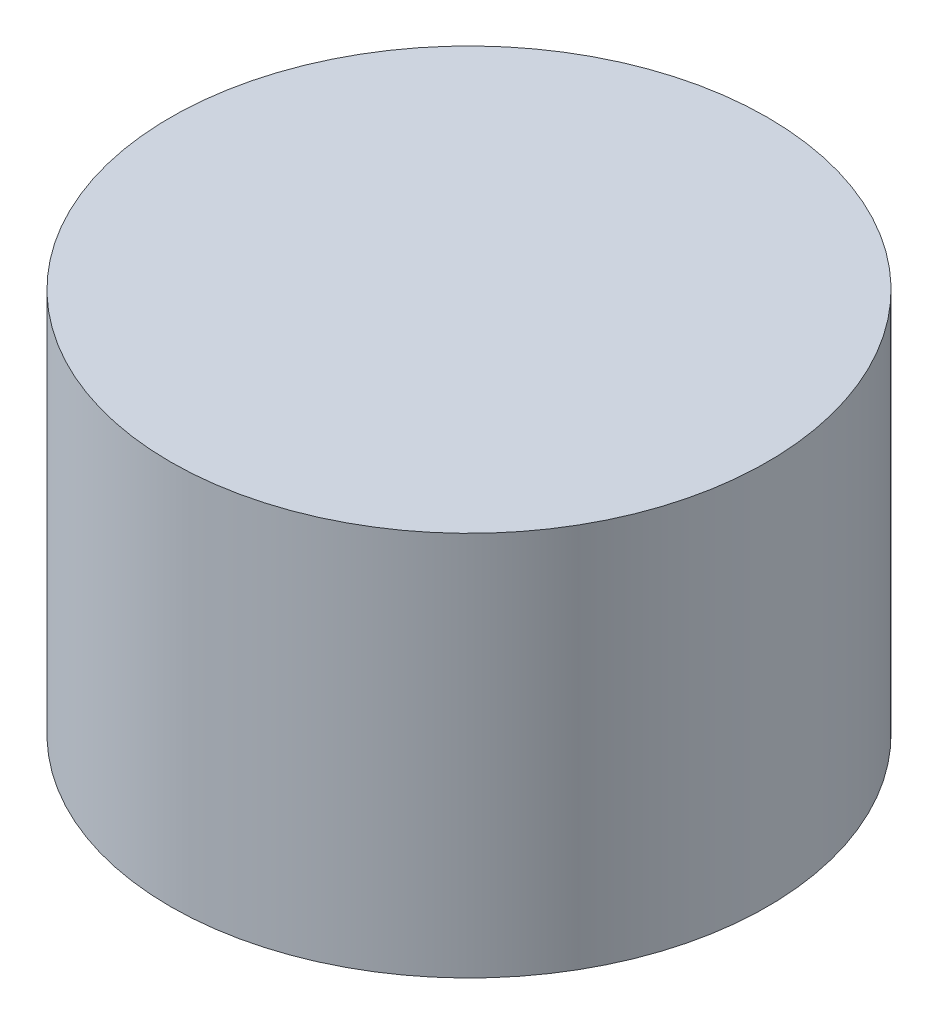
SolidWorks part; units mm, degrees
material "Natural Rubber"
ref_plane "Front Plane" through (0, 0, 0) normal (0, 0, 1) x (1, 0, 0)
ref_plane "Top Plane" through (0, 0, 0) normal (0, 1, 0) x (1, 0, 0)
ref_plane "Right Plane" through (0, 0, 0) normal (1, 0, 0) x (0, 0, -1)
sketch "Sketch1" plane through (0, 0, 0) normal (0, 1, 0) x (1, 0, 0)
  circle A0 centre (0, 0) radius 7.75
  dimension "D1" = 15.5
extrude "Boss-Extrude1" add sketch "Sketch1" along normal blind 10
